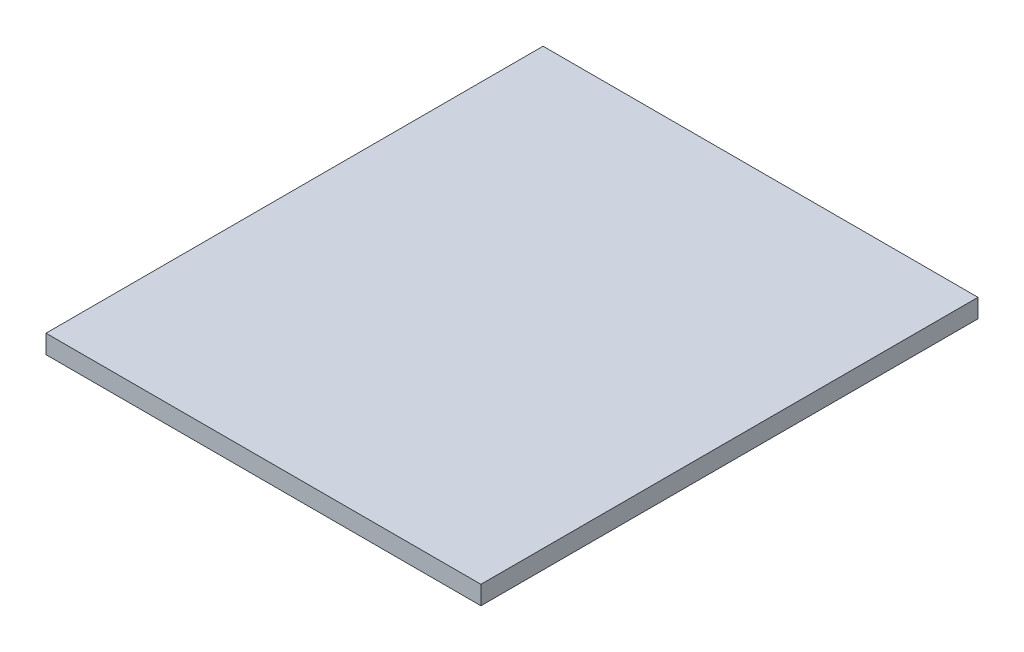
SolidWorks part; units mm, degrees
ref_plane "Plan de face" through (0, 0, 0) normal (0, 0, 1) x (1, 0, 0)
ref_plane "Plan de dessus" through (0, 0, 0) normal (0, 1, 0) x (1, 0, 0)
ref_plane "Plan de droite" through (0, 0, 0) normal (1, 0, 0) x (0, 0, -1)
sketch "Esquisse1" plane through (0, 0, 0) normal (0, 1, 0) x (1, 0, 0)
  line L1 (-35, -40) -> (35, -40)
  line L2 (-35, -40) -> (-35, 40)
  line L3 (-35, 40) -> (35, 40)
  line L4 (35, -40) -> (35, 40)
  line L5 (-35, -40) -> (35, 40) construction
  line L6 (-35, 40) -> (35, -40) construction
  point P0 (0, 0)
  dimension "D1" = 70
  dimension "D2" = 80
extrude "Boss.-Extru.1" add sketch "Esquisse1" along normal blind 3 contours L2 L3 L4 L1
